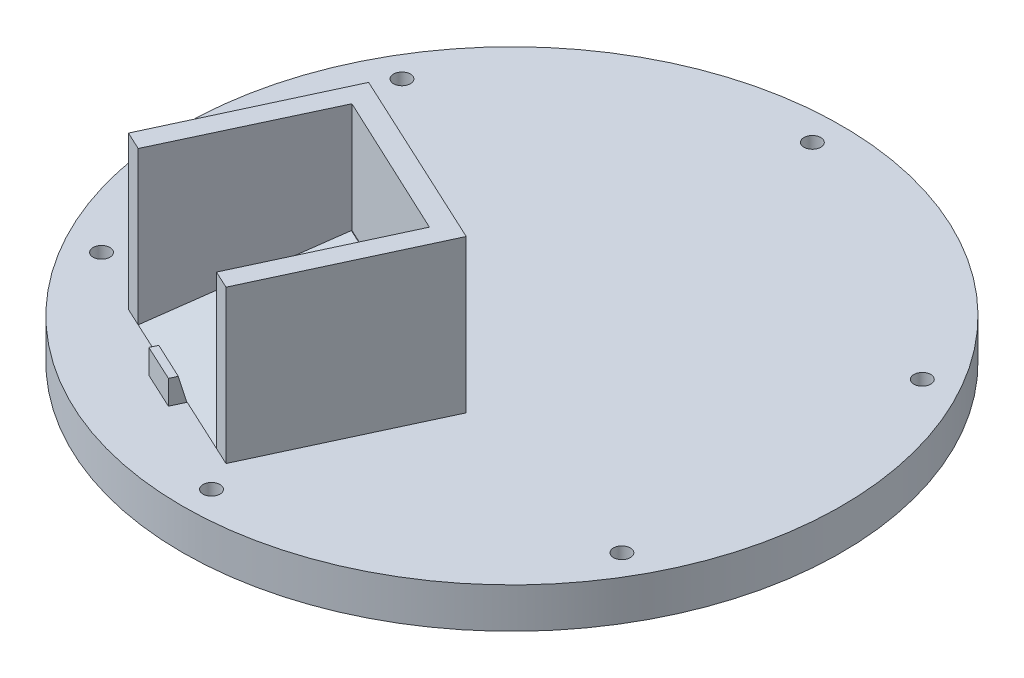
SolidWorks part; units mm, degrees
ref_plane "Front Plane" through (0, 0, 0) normal (0, 0, 1) x (1, 0, 0)
ref_plane "Top Plane" through (0, 0, 0) normal (0, 1, 0) x (1, 0, 0)
ref_plane "Right Plane" through (0, 0, 0) normal (1, 0, 0) x (0, 0, -1)
sketch "Sketch1" plane through (0, 0, 0) normal (0, 1, 0) x (1, 0, 0)
  line L0 (-82, 0) -> (82, 0)
  line L1 (0, -82) -> (0, 82)
  circle A0 centre (0, 0) radius 82
  point P8 (-67, 0)
  point P10 (67, 0)
  point P13 (0, -67)
  point P16 (0, 67)
  dimension "D1" = 164
  dimension "D2" = 15
  dimension "D4" = 15
  dimension "D6" = 15
  dimension "D8" = 15
extrude "Boss-Extrude5" add sketch "Sketch1" along normal blind 10
ref_plane "Plane1" through (0, 10, 0) normal (0, 1, 0) x (1, 0, 0)
sketch "Sketch9" plane through (0, 10, 0) normal (0, 1, 0) x (1, 0, 0)
  circle A0 centre (0, 0) radius 74.75
  point P3 (0, 74.75)
  point P4 (0, 74.75)
  dimension "D1" = 149.5
ref_plane "Plane3" through (0, 10, 0) normal (0, 1, 0) x (1, 0, 0)
sketch "Sketch14" plane through (0, 10, 0) normal (0, 1, 0) x (1, 0, 0)
  line L0 (-49.0892, -46.3303) -> (-3.7435, -67.3961)
  line L1 (-49.0892, -46.3303) -> (-30.13, -5.5192)
  line L2 (-30.13, -5.5192) -> (15.2157, -26.585)
  line L3 (-3.7435, -67.3961) -> (15.2157, -26.585)
  line L4 (-44.5547, -48.4369) -> (-27.6056, -12.2053)
  line L5 (-27.6056, -12.2053) -> (8.626, -29.1544)
  line L6 (8.626, -29.1544) -> (-8.1817, -65.3343)
  circle A0 centre (0, 0) radius 67.5
  point P7 (-44.5547, -48.4369)
  dimension "D1" = 135
  dimension "D2" = 50
  dimension "D3" = 5
  dimension "D4" = 45
  dimension "D5" = 90
  dimension "D6" = 50
  dimension "D7" = 40
  dimension "D8" = 40
hole_wizard "Tapped Hole for M4x0.7 Helicoil4" positions "Sketch15" profile "Sketch16" tap size "M4x0.7" standard "Helicoil® Metric" end condition through all
sketch "Sketch15" plane through (0, 10, 0) normal (0, 1, 0) x (1, 0, 0)
  point P0 (0, 74.75)
sketch "Sketch16" plane through (0, 10, -74.75) normal (1, 0, 0) x (0, 0, 1)
  line L0 (0, 0) -> (0, 10)
  line L1 (0, 10) -> (2.1, 10)
  line L2 (2.1, 10) -> (2.1, 0)
  line L5 (2.1, 0) -> (0, 0)
  line L11 (0, -6.35) -> (0, 107.95) construction
  dimension "Thru Tap Drill Dia." = 4.2
  dimension "Thru Tap Drill Depth" = 10
cosmetic thread "Hole Thread7" parameters "D1"=4.7, "D2"=5.007
pattern_circular "CirPattern5" count 6 over 360 about axis through (0, 0, 0) along (0, 1, 0) of "Tapped Hole for M4x0.7 Helicoil4"
ref_plane "Plane4" through (0, 10, 0) normal (0, 1, 0) x (1, 0, 0)
ref_plane "Plane5" through (0, 10, 0) normal (0, 1, 0) x (1, 0, 0)
sketch "Sketch27" plane through (0, 10, 0) normal (0, 1, 0) x (1, 0, 0)
  line L0 (-44.5547, -48.4369) -> (-27.6056, -12.2053)
  line L1 (-27.6056, -12.2053) -> (8.626, -29.1544)
  line L2 (8.626, -29.1544) -> (-8.1817, -65.3343)
  line L3 (-8.1817, -65.3343) -> (-44.5547, -48.4369)
extrude "Boss-Extrude7" add sketch "Sketch27" along normal blind 10.7
ref_plane "Plane6" through (18.2346, 0, 8.4711) normal (0.9069, 0, 0.4213) x (0.4213, 0, -0.9069)
sketch "Sketch28" plane through (18.2346, 0, 8.4711) normal (0.9069, 0, 0.4213) x (0.4213, 0, -0.9069)
  line L0 (-62.6997, 10) -> (-22.8062, 20.7)
  line L1 (-22.8062, 20.7) -> (-22.8062, 10) construction
  line L2 (-62.6997, 20.7) -> (-22.8062, 20.7) construction
  line L3 (-22.8062, 20.7) -> (-62.6997, 20.7)
  line L4 (-62.6997, 20.7) -> (-62.6997, 10) construction
  line L5 (-62.6997, 20.7) -> (-62.6997, 10)
extrude "Cut-Extrude1" cut sketch "Sketch28" against normal through all
extrude "Boss-Extrude8" add sketch "Sketch14" along normal blind 38 contours L5 L6 L0 L3 L2 L1 L4
ref_plane "Plane7" through (0, 10, 0) normal (0, 1, 0) x (1, 0, 0)
sketch "Sketch29" plane through (0, 10, 0) normal (0, 1, 0) x (1, 0, 0)
  line L0 (-32.3652, -57.981) -> (-23.2553, -62.2131)
  line L1 (-30.8822, -54.7886) -> (-32.3652, -57.981)
  line L2 (-44.5547, -48.4369) -> (-8.1817, -65.3343) construction
  line L3 (-49.0892, -46.3303) -> (-3.7435, -67.3961) construction
  line L4 (-23.2553, -62.2131) -> (-21.7723, -59.0207)
  line L5 (-21.7723, -59.0207) -> (-30.8822, -54.7886)
  dimension "D1" = 90
  dimension "D2" = 3.5201
extrude "Boss-Extrude9" add sketch "Sketch29" along normal blind 6
ref_plane "Plane9" through (-17.9647, 0, -8.4038) normal (0.9058, 0, 0.4237) x (0.4237, 0, -0.9058)
sketch "Sketch31" plane through (-17.9647, 0, -8.4038) normal (0.9058, 0, 0.4237) x (0.4237, 0, -0.9058)
  line L0 (-62.7527, 10) -> (-55.882, 11.8428)
  line L1 (-62.7527, 10) -> (-22.8591, 20.7) construction
  line L2 (-62.7527, 10) -> (-66.9007, 25.4654)
  line L3 (-64.8267, 17.7327) -> (-59.7262, 19.1007)
  line L4 (-59.7262, 19.1007) -> (-57.6163, 11.2341)
  line L5 (-62.33, 10.1134) -> (-62.2764, 18.4167)
  dimension "D2" = 90
extrude "Cut-Extrude2" cut sketch "Sketch31" along normal blind 30
